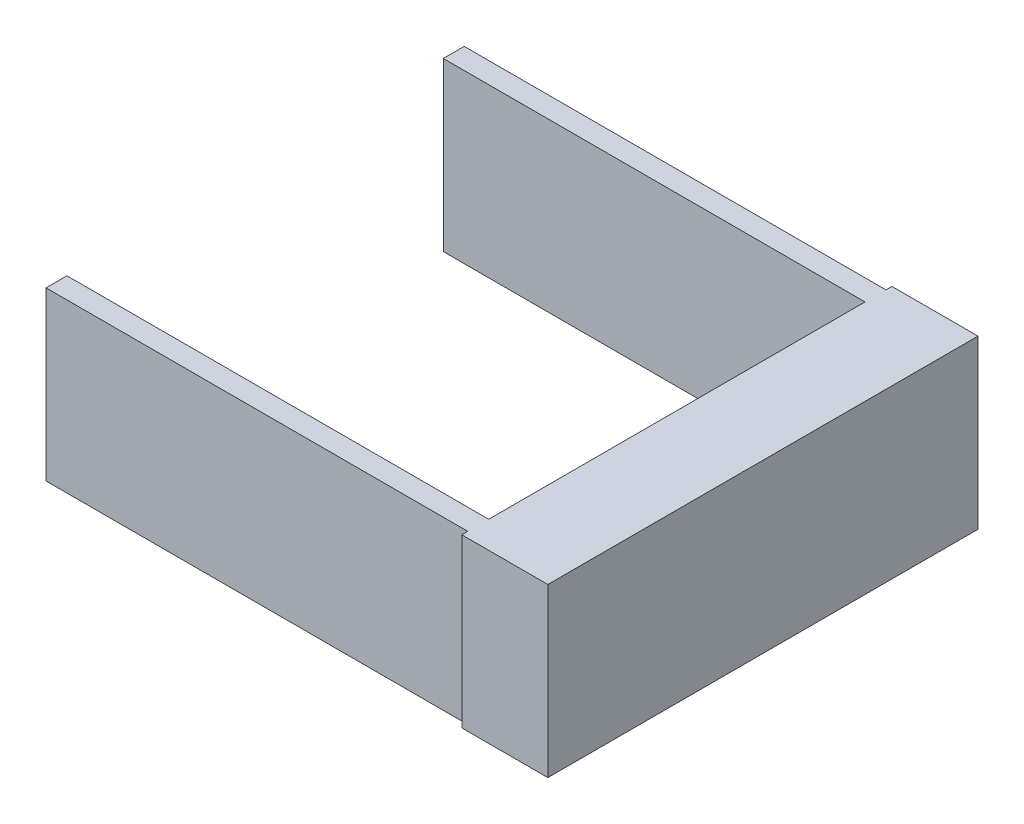
SolidWorks part; units mm, degrees
ref_plane "Front Plane" through (0, 0, 0) normal (0, 0, 1) x (1, 0, 0)
ref_plane "Top Plane" through (0, 0, 0) normal (0, 1, 0) x (1, 0, 0)
ref_plane "Right Plane" through (0, 0, 0) normal (1, 0, 0) x (0, 0, -1)
sketch "Sketch1" plane through (0, 0, 0) normal (0, 1, 0) x (1, 0, 0)
  line L0 (20.5945, 31.5) -> (20.5945, -31.5)
  line L5 (35, 36) -> (20.5945, 36)
  line L6 (35, 36) -> (35, -36)
  line L7 (35, -36) -> (20.5945, -36)
  line L8 (20.5945, 36) -> (20.5945, 35)
  line L9 (-50, -31.5) -> (20.5945, -31.5)
  line L10 (-50, -31.5) -> (-50, -35)
  line L13 (-50, 35) -> (20.5945, 35)
  line L14 (-50, 35) -> (-50, 31.5)
  line L15 (-50, 31.5) -> (20.5945, 31.5)
  line L18 (-50, -31.5) -> (20.5945, -31.5)
  line L19 (-50, -31.5) -> (-50, -35)
  line L20 (-50, -35) -> (20.5945, -35)
  line L22 (20.5945, -35) -> (20.5945, -36)
extrude "Boss-Extrude1" add sketch "Sketch1" along normal blind 28 contours L20 L22 L7 L6 L5 L8 L13 L14 L15 L0 L9 L10
